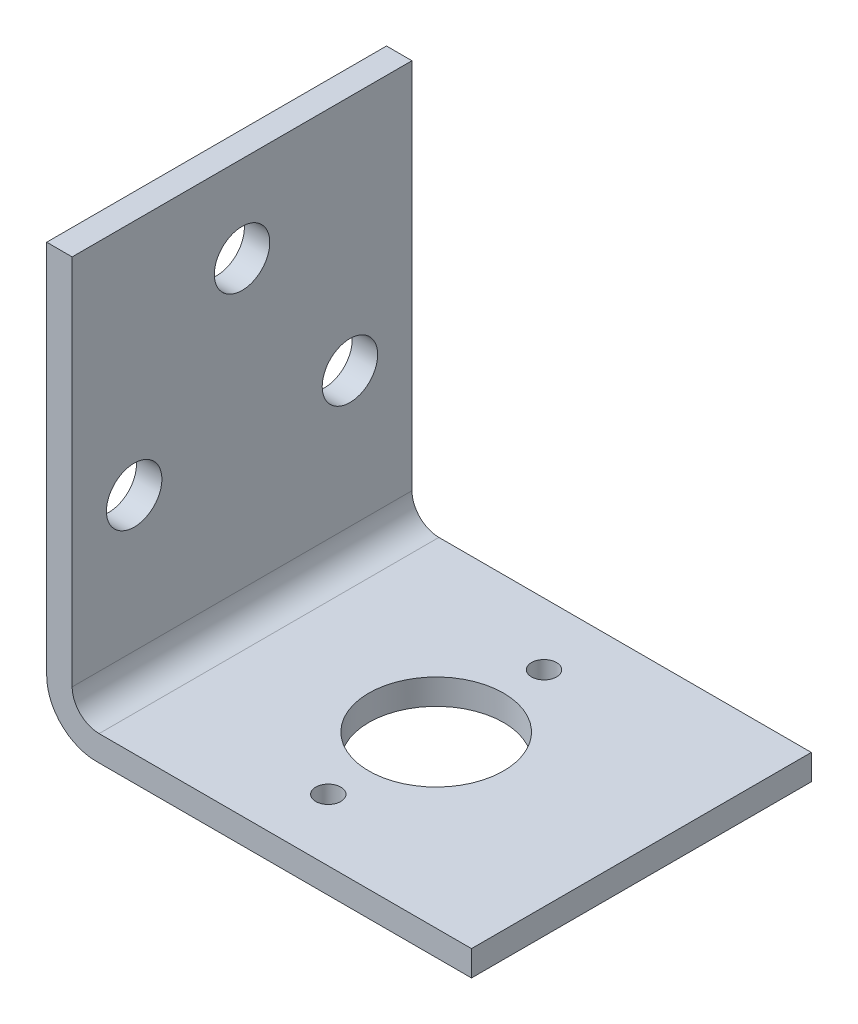
SolidWorks part; units mm, degrees
ref_plane "Front" through (0, 0, 0) normal (0, 0, 1) x (1, 0, 0)
ref_plane "Top" through (0, 0, 0) normal (0, 1, 0) x (1, 0, 0)
ref_plane "Right" through (0, 0, 0) normal (1, 0, 0) x (0, 0, -1)
sketch "Sketch2" plane through (0, 0, 0) normal (0, 0, 1) x (1, 0, 0)
  line L0 (0, 5.842) -> (0, 50.0126)
  line L1 (5.842, 0) -> (50.0126, 0)
  line L2 (6.1722, 2.9972) -> (50.0126, 2.9972)
  line L3 (2.9972, 6.1722) -> (2.9972, 50.0126)
  line L4 (0, 50.0126) -> (2.9972, 50.0126)
  line L5 (50.0126, 2.9972) -> (50.0126, 0)
  line L6 (2.9972, 2.9972) -> (50.0126, 2.9972) construction
  line L7 (2.9972, 2.9972) -> (2.9972, 50.0126) construction
  line L8 (0, 0) -> (0, 50.0126) construction
  line L9 (0, 0) -> (50.0126, 0) construction
  arc A0 (6.1722, 2.9972) -> (2.9972, 6.1722) centre (6.1722, 6.1722) cw
  arc A1 (0, 5.842) -> (5.842, 0) centre (5.842, 5.842) ccw
  point P13 (0, 0)
  dimension "D4" = 3.175
  dimension "D5" = 5.842
  dimension "D2" = 50.0126
  dimension "D3" = 50.0126
  dimension "D1" = 2.9972
extrude "Boss-Extrude1" add sketch "Sketch2" along normal blind 40.005
sketch "Sketch3" plane through (0, 0, 0) normal (0, -1, 0) x (1, 0, 0)
  line L0 (50.0126, 20.0025) -> (5.842, 20.0025) construction
  line L1 (50.0126, 40.005) -> (50.0126, 0) construction
  line L2 (5.842, 40.005) -> (5.842, 0) construction
  line L3 (0, 40.005) -> (0, 0) construction
  circle A0 centre (25.85, 32.7025) radius 1.4732
  circle A1 centre (25.85, 7.3025) radius 1.4732
  circle A2 centre (25.85, 20.0025) radius 7.9375
  dimension "D1" = 2.9464
  dimension "D4" = 15.875
  dimension "D2" = 25.4
  dimension "D3" = 25.85
extrude "4-40 For Nut Horizontal" cut sketch "Sketch3" against normal through all and the other way through all
sketch "Sketch4" plane through (0, 0, 0) normal (-1, 0, 0) x (0, 0, 1)
  line L0 (7.3025, 22.0726) -> (32.7025, 22.0726) construction
  line L2 (40.005, 50.0126) -> (0, 50.0126) construction
  circle A0 centre (7.3025, 22.0726) radius 3.2639
  circle A1 centre (32.7025, 22.0726) radius 3.2639
  circle A2 centre (20.0025, 39.8526) radius 3.2639
  point P4 (20.0025, 50.0126)
  point P5 (20.0025, 22.0726)
  dimension "D1" = 25.4
  dimension "D2" = 6.5278
  dimension "D4" = 17.78
  dimension "D3" = 27.94
extrude "1/4-20 Mounting" cut sketch "Sketch4" against normal through all
equation "\"D5@Sketch2\"=\"D4@Sketch2\"+.105"
